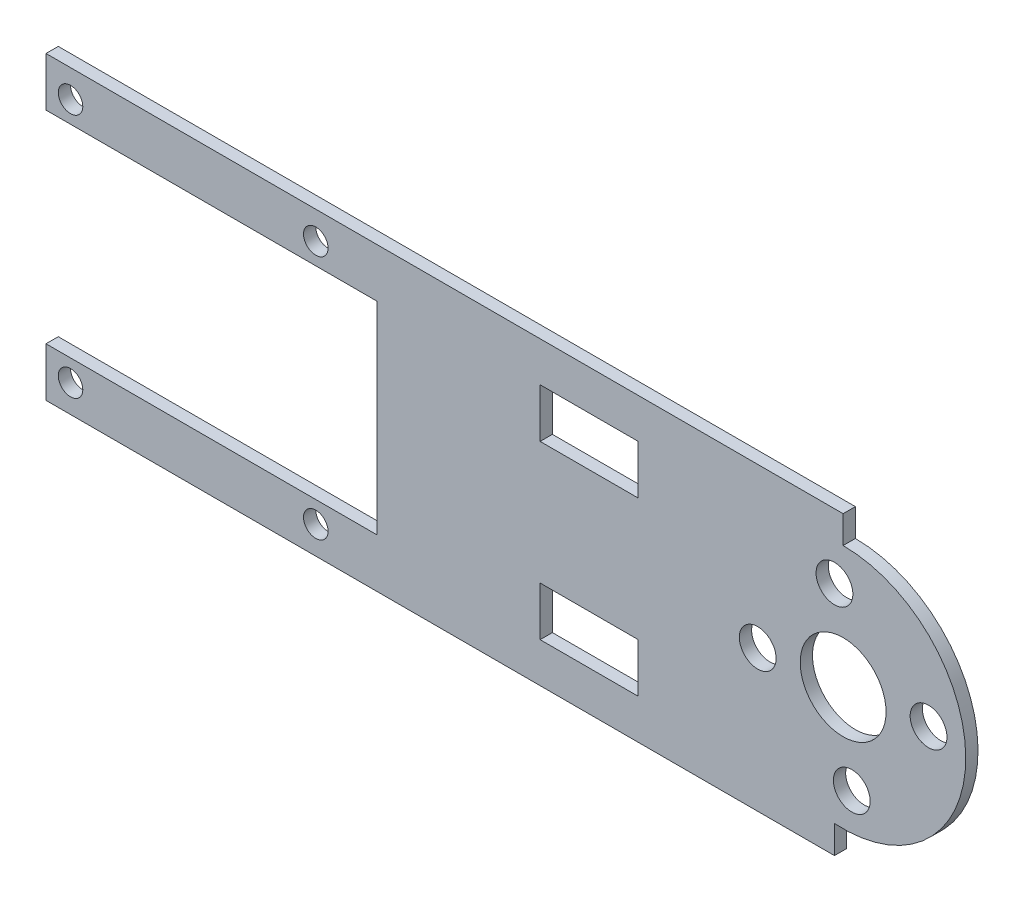
SolidWorks part; units mm, degrees
ref_plane "Front Plane" through (0, 0, 0) normal (0, 0, 1) x (1, 0, 0)
ref_plane "Top Plane" through (0, 0, 0) normal (0, 1, 0) x (1, 0, 0)
ref_plane "Right Plane" through (0, 0, 0) normal (1, 0, 0) x (0, 0, -1)
sketch "Sketch1" plane through (0, 0, 0) normal (0, 0, 1) x (1, 0, 0)
  line L1 (-4.1267, 12.25) -> (5.8733, 12.25)
  line L3 (-4.1267, -12.25) -> (5.8733, -12.25)
  line L5 (-4.1267, 12.25) -> (-24.1267, 12.25)
  line L6 (-24.1267, 12.25) -> (-24.1267, 8.25)
  line L12 (5.8733, 12.25) -> (40.8733, 12.25)
  line L13 (40.8733, 12.25) -> (40.8733, 10)
  line L14 (40.1665, -12.25) -> (5.8733, -12.25)
  line L15 (-24.1267, 8.25) -> (2.8733, 8.25)
  line L16 (40.1665, -9.975) -> (40.1665, -12.25)
  line L17 (16.1665, 9) -> (24.1665, 9)
  line L18 (16.1665, 9) -> (16.1665, 5)
  line L19 (16.1665, 5) -> (24.1665, 5)
  line L20 (24.1665, 9) -> (24.1665, 5)
  line L21 (16.1665, 9) -> (24.1665, 5) construction
  line L22 (16.1665, 5) -> (24.1665, 9) construction
  line L23 (16.1665, -5) -> (24.1665, -5)
  line L24 (16.1665, -5) -> (16.1665, -9)
  line L25 (16.1665, -9) -> (24.1665, -9)
  line L26 (24.1665, -5) -> (24.1665, -9)
  line L27 (16.1665, -5) -> (24.1665, -9) construction
  line L28 (16.1665, -9) -> (24.1665, -5) construction
  line L29 (2.8733, 8.25) -> (2.8733, -8.25)
  line L30 (2.8733, -8.25) -> (-24.1267, -8.25)
  line L31 (-24.1267, -8.25) -> (-24.1267, -12.25)
  line L32 (-24.1267, -12.25) -> (-4.1267, -12.25)
  arc A2 (40.1665, -9.975) -> (40.8733, 10) centre (40.8733, 0) ccw
  circle A3 centre (40.1664, 6.9642) radius 1.5
  circle A4 centre (47.8375, 0.7069) radius 1.5
  circle A5 centre (41.5802, -6.9642) radius 1.5
  circle A6 centre (33.9091, -0.7069) radius 1.5
  circle A7 centre (40.8733, 0) radius 3.5
  circle A8 centre (-2.1267, 10) radius 1
  circle A9 centre (-2.1267, -10) radius 1
  circle A10 centre (-22.1267, 10) radius 1
  circle A11 centre (-22.1267, -10) radius 1
  point P4 (0, 0)
  point P22 (20.1665, 7)
  point P35 (20.1665, -7)
  dimension "D3" = 2
  dimension "D4" = 2
  dimension "D11" = 20
  dimension "D12" = 3
  dimension "D15" = 7
  dimension "D8" = 2
  dimension "D16" = 2
  dimension "D5" = 43
  dimension "D6" = 24.5
  dimension "D7" = 24.5
  dimension "D9" = 12.25
  dimension "D10" = 35
  dimension "D13" = 7
  dimension "D17" = 20
  dimension "D18" = 5
  dimension "D19" = 20
  dimension "D20" = 4
  dimension "D21" = 4
  dimension "D22" = 8
  dimension "D23" = 8
  dimension "D24" = 10
  dimension "D25" = 10
  dimension "D26" = 20
  dimension "D27" = 20
  dimension "D28" = 4
  dimension "D29" = 4
  dimension "D14" = 4
extrude "Boss-Extrude1" add sketch "Sketch1" along normal blind 1
